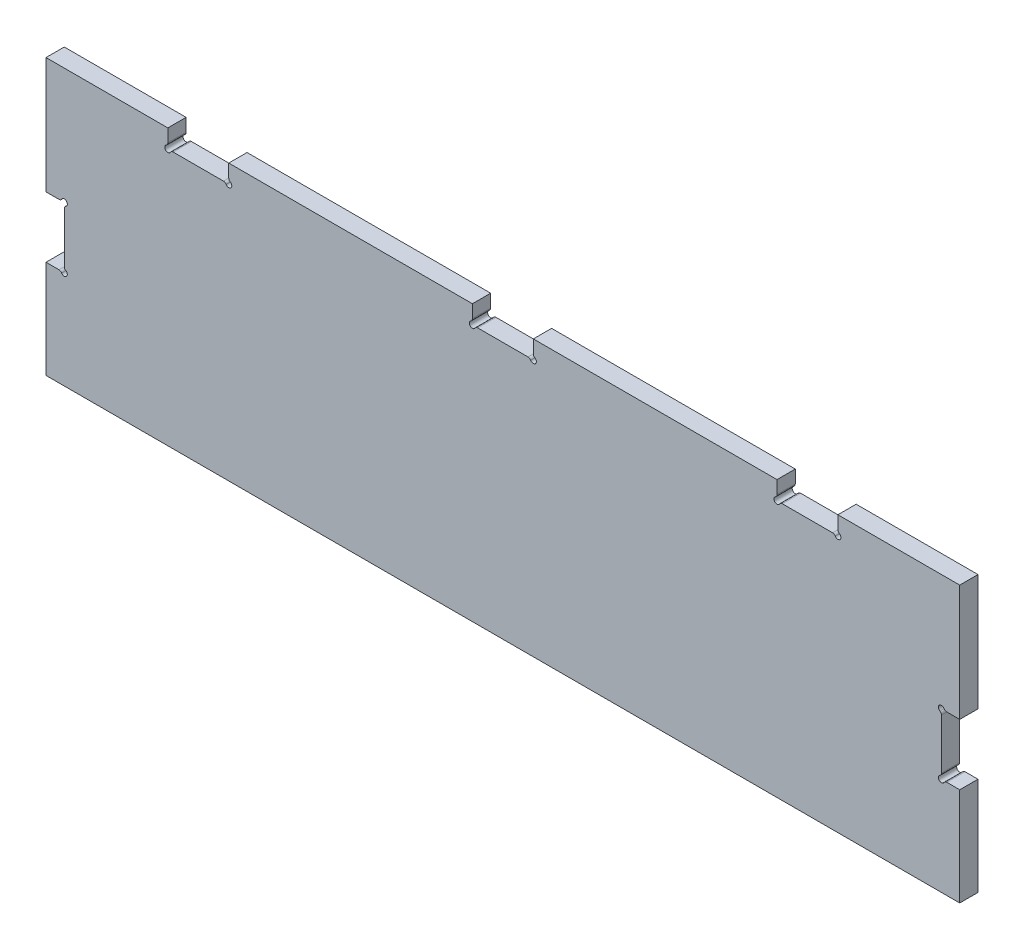
SolidWorks part; units mm, degrees
ref_plane "Front Plane" through (0, 0, 0) normal (0, 0, 1) x (1, 0, 0)
ref_plane "Top Plane" through (0, 0, 0) normal (0, 1, 0) x (1, 0, 0)
ref_plane "Right Plane" through (0, 0, 0) normal (1, 0, 0) x (0, 0, -1)
sketch "Sketch1" plane through (0, 0, 0) normal (0, 0, 1) x (1, 0, 0)
  line L0 (75, 3) -> (55, 3)
  line L1 (55, 0) -> (55, 3)
  line L2 (55, 0) -> (45, 0)
  line L3 (45, 0) -> (45, 3)
  line L4 (45, 3) -> (5, 3)
  line L5 (5, 0) -> (5, 3)
  line L6 (5, 0) -> (-5, 0)
  line L7 (-5, 0) -> (-5, 3)
  line L8 (-5, 3) -> (-45, 3)
  line L9 (-45, 0) -> (-45, 3)
  line L10 (-45, 0) -> (-55, 0)
  line L11 (-55, 0) -> (-55, 3)
  line L12 (-55, 3) -> (-75, 3)
  line L14 (-75, -42.2) -> (75, -42.2)
  line L22 (0, 0) -> (0, -42.2) construction
  line L30 (-75, -42.2) -> (-75, -21.1) construction
  line L31 (-75, -21.1) -> (-72, -21.1) construction
  line L32 (-72, -26.1) -> (-72, -16.1)
  line L33 (-72, -16.1) -> (-75, -16.1)
  line L34 (-72, -26.1) -> (-75, -26.1)
  line L35 (-75, 3) -> (-75, -16.1)
  line L36 (-75, -26.1) -> (-75, -42.2)
  line L37 (72, -26.1) -> (75, -26.1)
  line L38 (75, -26.1) -> (75, -42.2)
  line L39 (72, -26.1) -> (72, -16.1)
  line L40 (72, -16.1) -> (75, -16.1)
  line L41 (75, 3) -> (75, -16.1)
  point P14 (0, 0)
  point P23 (-72, -21.1)
  dimension "D1" = 45.2
  dimension "D2" = 21.1
  dimension "D3" = 3
  dimension "D4" = 10
  dimension "D5" = 20
  dimension "D6" = 10
  dimension "D7" = 3
  dimension "D8" = 40
  dimension "D9" = 10
  dimension "D10" = 150
  dimension "D11" = 40
  dimension "D12" = 10
  dimension "D13" = 20
  dimension "D14" = 3
  dimension "D15" = 3
  dimension "D16" = 3
  dimension "D17" = 3
  dimension "D18" = 3
extrude "Boss-Extrude1" add sketch "Sketch1" along normal mid plane 3
sketch "Sketch2" plane through (0, 0, 1.5) normal (0, 0, 1) x (1, 0, 0)
  circle A0 centre (-55, 0) radius 0.5
  circle A1 centre (-45, 0) radius 0.5
  circle A2 centre (-5, 0) radius 0.5
  circle A3 centre (5, 0) radius 0.5
  circle A4 centre (45, 0) radius 0.5
  circle A5 centre (55, 0) radius 0.5
  circle A6 centre (72, -16.1) radius 0.5
  circle A7 centre (72, -26.1) radius 0.5
  circle A8 centre (-72, -26.1) radius 0.5
  circle A9 centre (-72, -16.1) radius 0.5
  dimension "D1" = 1
extrude "Cut-Extrude1" cut sketch "Sketch2" against normal through all
fillet "Fillet1" radius 0.5 20 edges at (72.5, -26.1, 0) (72, -25.6, 0) (72, -16.6, 0) (72.5, -16.1, 0) (55, 0.5, 0) (54.5, 0, 0) (45, 0.5, 0) (45.5, 0, 0) (-4.5, 0, 0) (-5, 0.5, 0) (4.5, 0, 0) (5, 0.5, 0) (-45, 0.5, 0) (-45.5, 0, 0) (-54.5, 0, 0) (-55, 0.5, 0) (-72, -16.6, 0) (-72.5, -16.1, 0) (-72.5, -26.1, 0) (-72, -25.6, 0)
